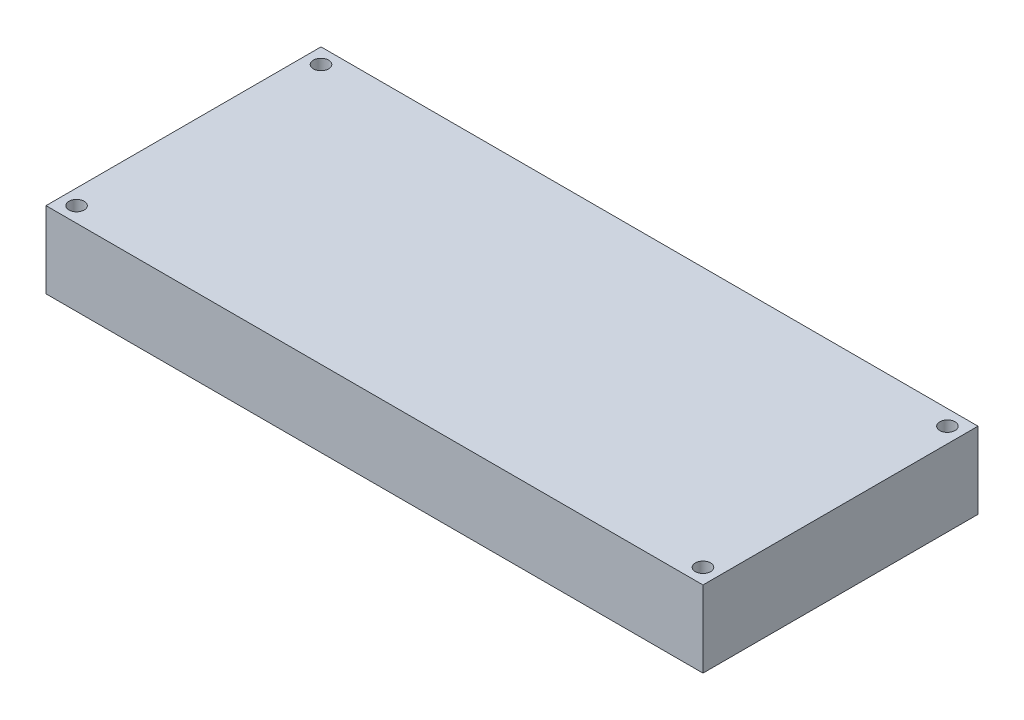
SolidWorks part; units mm, degrees
ref_plane "Piano frontale" through (0, 0, 0) normal (0, 0, 1) x (1, 0, 0)
ref_plane "Piano superiore" through (0, 0, 0) normal (0, 1, 0) x (1, 0, 0)
ref_plane "Piano destro" through (0, 0, 0) normal (1, 0, 0) x (0, 0, -1)
sketch "Schizzo1" plane through (0, 0, 0) normal (0, 1, 0) x (1, 0, 0)
  line L1 (-21.5, -9) -> (21.5, -9)
  line L2 (-21.5, -9) -> (-21.5, 9)
  line L3 (-21.5, 9) -> (21.5, 9)
  line L4 (21.5, -9) -> (21.5, 9)
  line L5 (-21.5, -9) -> (21.5, 9) construction
  line L6 (-21.5, 9) -> (21.5, -9) construction
  point P0 (0, 0)
  dimension "D1" = 43
  dimension "D2" = 18
extrude "Estrusione-Estrusione1" add sketch "Schizzo1" along normal blind 5
sketch "Schizzo2" plane through (0, 5, 0) normal (0, 1, 0) x (1, 0, 0)
  line L0 (-21.5, 9) -> (-21.5, -9) construction
  line L1 (21.5, 9) -> (-21.5, 9) construction
  line L2 (-21.5, -9) -> (21.5, -9) construction
  line L3 (21.5, -9) -> (21.5, 9) construction
  circle A0 centre (-20.5, 8) radius 0.5
  circle A1 centre (20.5, 8) radius 0.5
  circle A2 centre (20.5, -8) radius 0.5
  circle A3 centre (-20.5, -8) radius 0.5
  dimension "D1" = 1
  dimension "D2" = 1
  dimension "D3" = 1
  dimension "D4" = 1
  dimension "D5" = 1
  dimension "D6" = 1
  dimension "D7" = 1
  dimension "D8" = 1
  dimension "D9" = 1
  dimension "D10" = 1
  dimension "D11" = 1
  dimension "D12" = 1
extrude "Taglio-Estrusione1" cut sketch "Schizzo2" against normal blind 5
